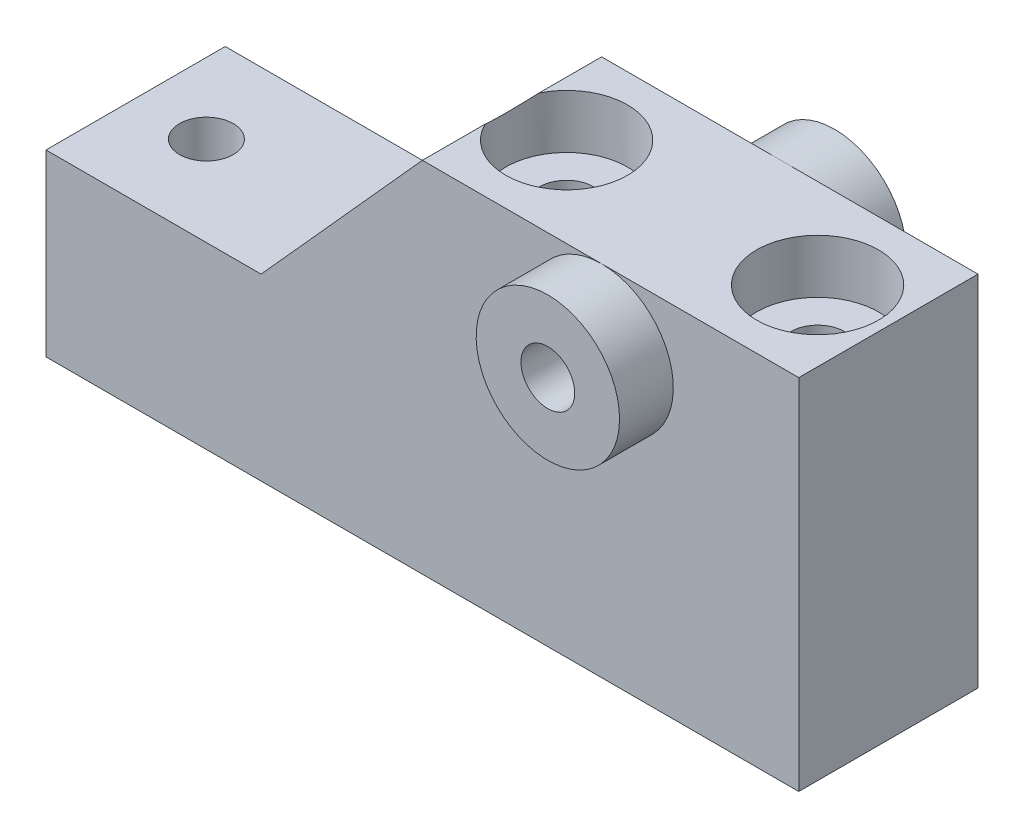
SolidWorks part; units mm, degrees
ref_plane "Front" through (0, 0, 0) normal (0, 0, 1) x (1, 0, 0)
ref_plane "Top" through (0, 0, 0) normal (0, 1, 0) x (1, 0, 0)
ref_plane "Right" through (0, 0, 0) normal (1, 0, 0) x (0, 0, -1)
sketch "草图1" plane through (0, 0, 0) normal (0, 0, 1) x (1, 0, 0)
  line L0 (0, 0) -> (42, 0)
  line L1 (42, 0) -> (42, 20)
  line L2 (21, 20) -> (42, 20)
  line L3 (0, 10) -> (0, 0)
  line L4 (0, 10) -> (12, 10)
  line L5 (12, 10) -> (21, 20)
  circle A0 centre (31, 16) radius 1.5
extrude "凸台-拉伸1" add sketch "草图1" along normal blind 10
sketch "草图2" plane through (0, 0, 0) normal (0, -1, 0) x (1, 0, 0)
  circle A1 centre (38.05, 5) radius 1.5
  circle A2 centre (3.95, 5) radius 1.5
  circle A3 centre (24.05, 5) radius 1.5
extrude "切除-拉伸1" cut sketch "草图2" against normal blind 28
sketch "草图3" plane through (0, 20, 0) normal (0, 1, 0) x (1, 0, 0)
  circle A0 centre (24.05, -5) radius 3.4
  circle A1 centre (38.05, -5) radius 3.4
extrude "切除-拉伸2" cut sketch "草图3" against normal blind 3
sketch "草图4" plane through (0, 0, 10) normal (0, 0, 1) x (1, 0, 0)
  circle A0 centre (31, 16) radius 4
  circle A1 centre (31, 16) radius 1.5
extrude "凸台-拉伸2" add sketch "草图4" along normal blind 3
sketch "草图5" plane through (0, 0, 0) normal (0, 0, -1) x (-1, 0, 0)
  circle A0 centre (-31, 16) radius 4
  circle A1 centre (-31, 16) radius 1.5
extrude "凸台-拉伸3" add sketch "草图5" along normal blind 3
